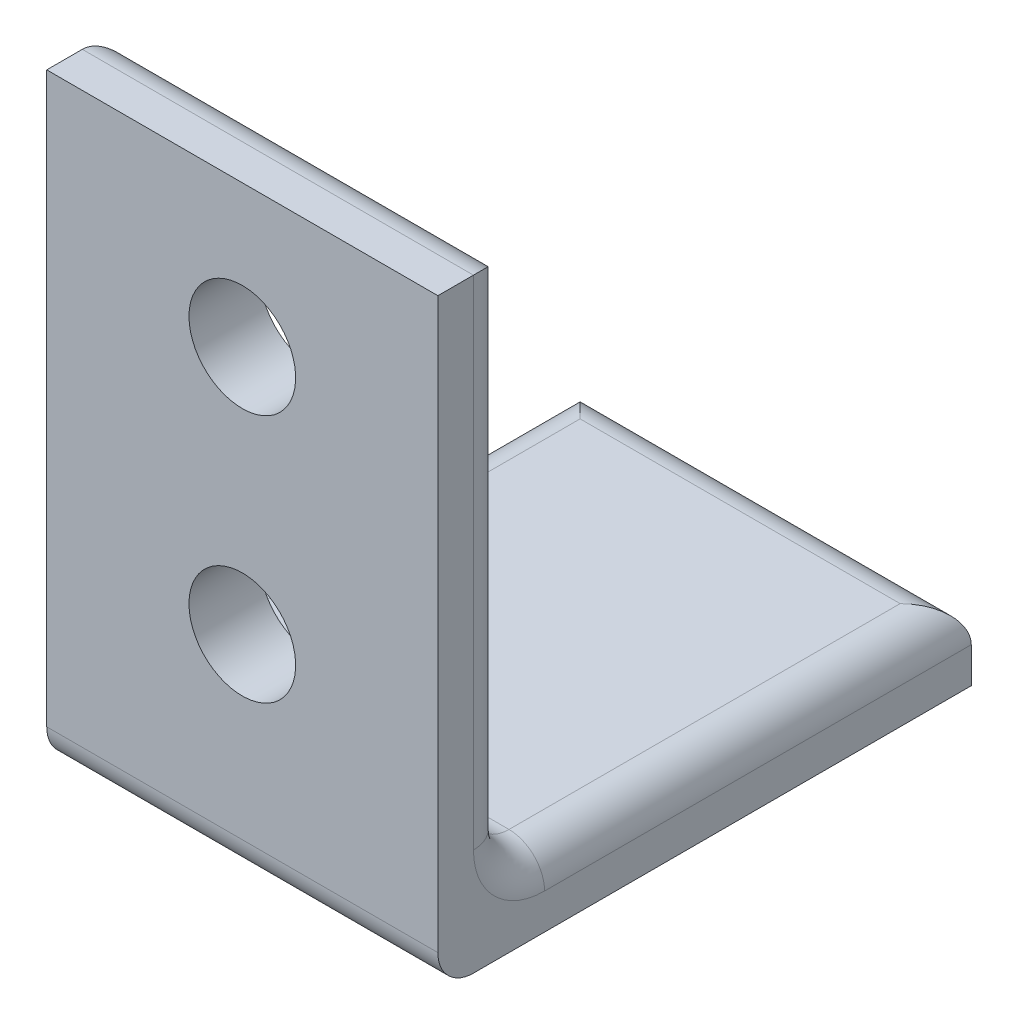
SolidWorks part; units mm, degrees
material "ABS"
ref_plane "Plano frontal" through (0, 0, 0) normal (0, 0, 1) x (1, 0, 0)
ref_plane "Plano superior" through (0, 0, 0) normal (0, 1, 0) x (1, 0, 0)
ref_plane "Plano direito" through (0, 0, 0) normal (1, 0, 0) x (0, 0, -1)
sketch "Esboço1" plane through (0, 0, 0) normal (0, 1, 0) x (1, 0, 0)
  line L1 (-31.4424, -26.6246) -> (-20.4424, -26.6246)
  line L2 (-31.4424, -26.6246) -> (-31.4424, -7.6246)
  line L3 (-31.4424, -7.6246) -> (-20.4424, -7.6246)
  line L4 (-20.4424, -26.6246) -> (-20.4424, -7.6246)
extrude "Ressalto-extrusão1" add sketch "Esboço1" along normal blind 2
sketch "Esboço2" plane through (0, 2, 0) normal (0, 1, 0) x (1, 0, 0)
  line L0 (-31.4424, -7.6246) -> (-31.4424, -26.6246) construction
  line L1 (-31.4424, -26.6246) -> (-20.4424, -26.6246)
  line L2 (-31.4424, -26.6246) -> (-31.4424, -24.6246)
  line L3 (-31.4424, -24.6246) -> (-20.4424, -24.6246)
  line L4 (-20.4424, -26.6246) -> (-20.4424, -24.6246)
  line L5 (-20.4424, -26.6246) -> (-20.4424, -7.6246) construction
extrude "Ressalto-extrusão2" add sketch "Esboço2" along normal blind 15
sketch "Esboço3" plane through (0, 0, 24.6246) normal (0, 0, -1) x (-1, 0, 0)
  line L0 (20.4424, 2) -> (31.4424, 2) construction
  line L1 (20.4424, 17) -> (31.4424, 17) construction
  line L2 (20.4424, 17) -> (20.4424, 2) construction
  circle A0 centre (25.9424, 6) radius 1.5
  circle A1 centre (25.9424, 13) radius 1.5
  point P6 (25.9424, 2)
  dimension "D1" = 4
  dimension "D2" = 4
  dimension "D3" = 5.5
  dimension "D4" = 5.5
extrude "Corte-extrusão1" cut sketch "Esboço3" against normal blind 15
sketch "Esboço4" plane through (0, 2, 0) normal (0, 1, 0) x (1, 0, 0)
  line L1 (-31.4424, -7.6246) -> (-20.4424, -7.6246)
  line L2 (-31.4424, -7.6246) -> (-31.4424, -11.6246)
  line L3 (-31.4424, -11.6246) -> (-20.4424, -11.6246)
  line L4 (-20.4424, -7.6246) -> (-20.4424, -11.6246)
extrude "Corte-extrusão2" cut sketch "Esboço4" against normal blind 15
fillet "Filete1" radius 1 2 edges at (-25.9424, 0, 26.6246) (-25.9424, 2, 24.6246)
fillet "Filete2" radius 1 8 edges at (-20.4424, 10, 24.6246) (-20.4424, 2.2929, 24.3317) (-31.4424, 10, 24.6246) (-31.4424, 2.2929, 24.3317) (-25.9424, 2, 11.6246) (-20.4424, 2, 17.6246) (-31.4424, 2, 17.6246) (-25.9424, 17, 24.6246)
